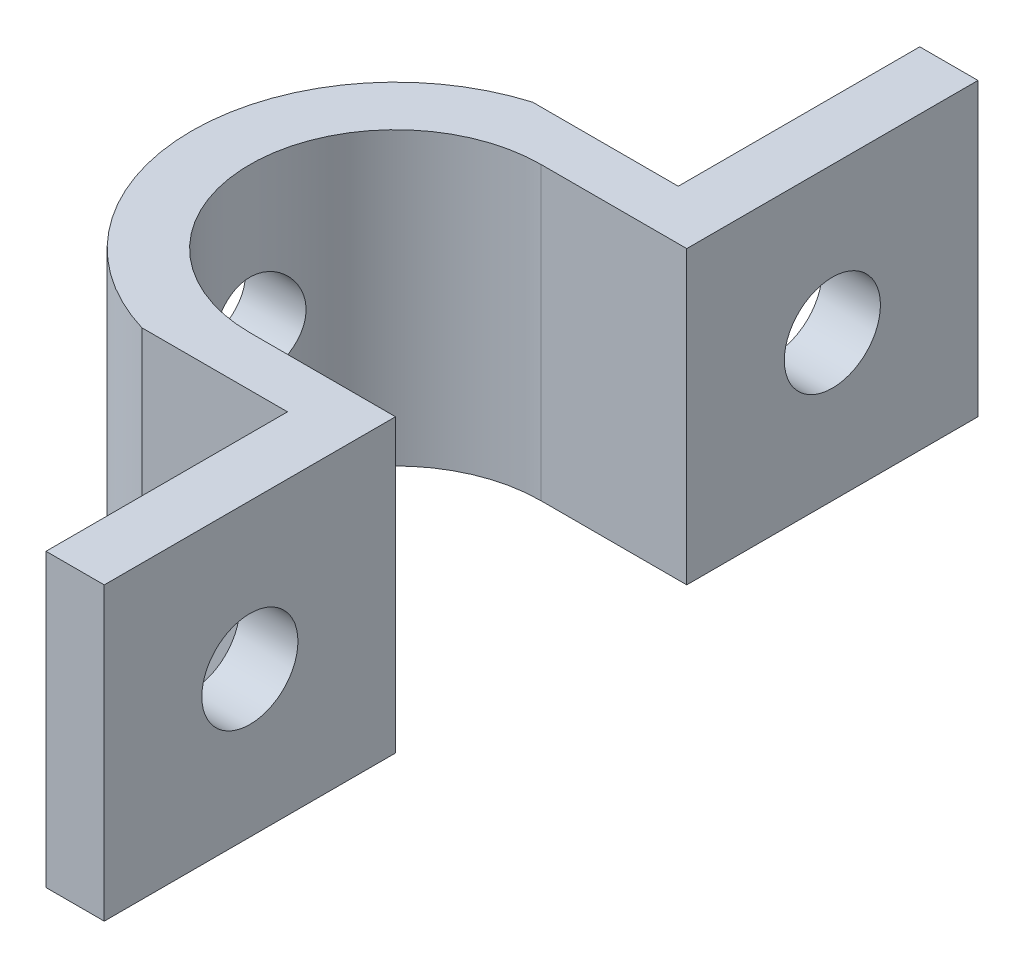
SolidWorks part; units mm, degrees
material "6063-T5"
ref_plane "前视基准面" through (0, 0, 0) normal (0, 0, 1) x (1, 0, 0)
ref_plane "上视基准面" through (0, 0, 0) normal (0, 1, 0) x (1, 0, 0)
ref_plane "右视基准面" through (0, 0, 0) normal (1, 0, 0) x (0, 0, -1)
other "Configuration Table"
sketch "草图1" plane through (0, 0, 0) normal (0, 1, 0) x (1, 0, 0)
  line L0 (0, 0) -> (0, -10)
  line L1 (0, -20) -> (0, -30)
  line L2 (-2, 0) -> (-2, -8.2918)
  line L3 (-2, -21.7082) -> (-2, -30)
  line L4 (-2, 0) -> (0, 0)
  line L5 (-2, -30) -> (0, -30)
  arc A0 (0, -10) -> (0, -20) centre (0, -15) ccw
  arc A1 (-2, -8.2918) -> (-2, -21.7082) centre (0, -15) ccw
  dimension "5" = 5
  dimension "D1" = 10
  dimension "D2" = 10
  dimension "D4" = 2
extrude "凸台-拉伸1" add sketch "草图1" along normal blind 10
ref_plane "基准面3" through (-7, 0, 0) normal (-1, 0, 0) x (0, 0, 1)
sketch "草图11" plane through (-7, 0, 0) normal (-1, 0, 0) x (0, 0, 1)
  line L0 (15, 10) -> (15, 0) construction
  line L1 (21.7082, 10) -> (8.2918, 10) construction
  line L2 (8.2918, 0) -> (21.7082, 0) construction
  line L3 (8.2918, 5) -> (21.7082, 5) construction
  line L4 (8.2918, 10) -> (8.2918, 0) construction
  line L5 (21.7082, 10) -> (21.7082, 0) construction
  point P13 (15, 5)
hole_wizard "M3 螺纹孔的螺纹孔钻头2" positions "草图11" profile "草图14" hole size "M3" standard "GB" end condition through all
sketch "草图14" plane through (-7, 5, 15) normal (0, 1, 0) x (0, 0, 1)
  line L0 (0, 0) -> (0, 7)
  line L1 (0, 7) -> (1.25, 7)
  line L2 (1.25, 7) -> (1.25, 0.025)
  line L3 (1.25, 0.025) -> (1.275, 0)
  line L5 (1.275, 0) -> (0, 0)
  line L6 (-1.25, 0.025) -> (-1.275, 0) construction
  line L11 (0, -6.35) -> (0, 107.95) construction
  dimension "通孔孔直径" = 2.5
  dimension "通孔孔深度" = 7
  dimension "近端锥形沉头孔直径" = 2.55
  dimension "近端锥形沉头孔角度" = 90
sketch "草图15" plane through (0, 0, 0) normal (1, 0, 0) x (0, 0, -1)
  line L4 (-10, 0) -> (0, 0)
  line L5 (0, 0) -> (0, 10)
  line L6 (0, 10) -> (-10, 10)
  line L7 (-10, 10) -> (-10, 0)
  line L8 (-10, 0) -> (0, 0)
  line L9 (0, 0) -> (0, 10)
  line L10 (0, 10) -> (-10, 10)
  line L11 (-10, 10) -> (-10, 0)
  line L12 (-30, 0) -> (-20, 0)
  line L13 (-20, 0) -> (-20, 10)
  line L14 (-20, 10) -> (-30, 10)
  line L15 (-30, 10) -> (-30, 0)
  line L16 (-30, 0) -> (-20, 0)
  line L17 (-20, 0) -> (-20, 10)
  line L18 (-20, 10) -> (-30, 10)
  line L19 (-30, 10) -> (-30, 0)
  dimension "D1" = 0
  dimension "D2" = 0
extrude "凸台-拉伸2" add sketch "草图15" along normal blind 5
sketch "草图16" plane through (5, 0, 0) normal (1, 0, 0) x (0, 0, -1)
  line L0 (-10, 5) -> (0, 5) construction
  line L1 (-10, 10) -> (-10, 0) construction
  line L2 (0, 0) -> (0, 10) construction
  line L3 (-5, 10) -> (-5, 0) construction
  line L4 (0, 10) -> (-10, 10) construction
  line L5 (-10, 0) -> (0, 0) construction
  line L6 (-25, 10) -> (-25, 0) construction
  line L7 (-20, 10) -> (-30, 10) construction
  line L8 (-30, 0) -> (-20, 0) construction
  line L9 (-30, 5) -> (-20, 5) construction
  line L10 (-30, 10) -> (-30, 0) construction
  line L11 (-20, 10) -> (-20, 0) construction
  point P24 (-25, 5)
  point P26 (-5, 5)
hole_wizard "M3 螺纹孔的螺纹孔钻头1" positions "草图16" profile "草图18" hole size "M3" standard "GB" end condition through all
sketch "草图18" plane through (5, 5, 5) normal (0, 1, 0) x (0, 0, -1)
  line L0 (0, 0) -> (0, 12)
  line L1 (0, 12) -> (1.25, 12)
  line L2 (1.25, 12) -> (1.25, 0.025)
  line L3 (1.25, 0.025) -> (1.275, 0)
  line L5 (1.275, 0) -> (0, 0)
  line L6 (-1.25, 0.025) -> (-1.275, 0) construction
  line L11 (0, -6.35) -> (0, 107.95) construction
  dimension "通孔孔直径" = 2.5
  dimension "通孔孔深度" = 12
  dimension "近端锥形沉头孔直径" = 2.55
  dimension "近端锥形沉头孔角度" = 90
sketch "草图19" plane through (-2, 0, 0) normal (-1, 0, 0) x (0, 0, 1)
  line L4 (0, 0) -> (8.2918, 0)
  line L5 (8.2918, 0) -> (8.2918, 10)
  line L6 (8.2918, 10) -> (0, 10)
  line L7 (0, 10) -> (0, 0)
  line L8 (0, 0) -> (8.2918, 0)
  line L9 (8.2918, 0) -> (8.2918, 10)
  line L10 (8.2918, 10) -> (0, 10)
  line L11 (0, 10) -> (0, 0)
  line L12 (21.7082, 0) -> (30, 0)
  line L13 (30, 0) -> (30, 10)
  line L14 (30, 10) -> (21.7082, 10)
  line L15 (21.7082, 10) -> (21.7082, 0)
  line L16 (21.7082, 0) -> (30, 0)
  line L17 (30, 0) -> (30, 10)
  line L18 (30, 10) -> (21.7082, 10)
  line L19 (21.7082, 10) -> (21.7082, 0)
  dimension "D1" = 0
  dimension "D2" = 0
sketch "草图21" plane through (-2, 0, 0) normal (-1, 0, 0) x (0, 0, 1)
  line L4 (0, 0) -> (8.2918, 0)
  line L5 (8.2918, 0) -> (8.2918, 10)
  line L6 (8.2918, 10) -> (0, 10)
  line L7 (0, 10) -> (0, 0)
  line L8 (0, 0) -> (8.2918, 0)
  line L9 (8.2918, 0) -> (8.2918, 10)
  line L10 (8.2918, 10) -> (0, 10)
  line L11 (0, 10) -> (0, 0)
  line L12 (21.7082, 0) -> (30, 0)
  line L13 (30, 0) -> (30, 10)
  line L14 (30, 10) -> (21.7082, 10)
  line L15 (21.7082, 10) -> (21.7082, 0)
  line L16 (21.7082, 0) -> (30, 0)
  line L17 (30, 0) -> (30, 10)
  line L18 (30, 10) -> (21.7082, 10)
  line L19 (21.7082, 10) -> (21.7082, 0)
  dimension "D1" = 0
  dimension "D2" = 0
extrude "切除-拉伸2" cut sketch "草图21" against normal blind 5
sketch "草图23" plane through (3, 0, 0) normal (-1, 0, 0) x (0, 0, 1)
  circle A0 centre (25, 5) radius 1.65
  circle A1 centre (5, 5) radius 1.65
  dimension "D1" = 3.3
  dimension "D2" = 3.3
extrude "切除-拉伸3" cut sketch "草图23" against normal blind 10
sketch "草图24" plane through (-7, 0, 0) normal (-1, 0, 0) x (0, 0, 1)
  circle A0 centre (15, 5) radius 1.65
  point P2 (15, 5)
  dimension "D1" = 3.3
extrude "切除-拉伸4" cut sketch "草图24" against normal blind 10
